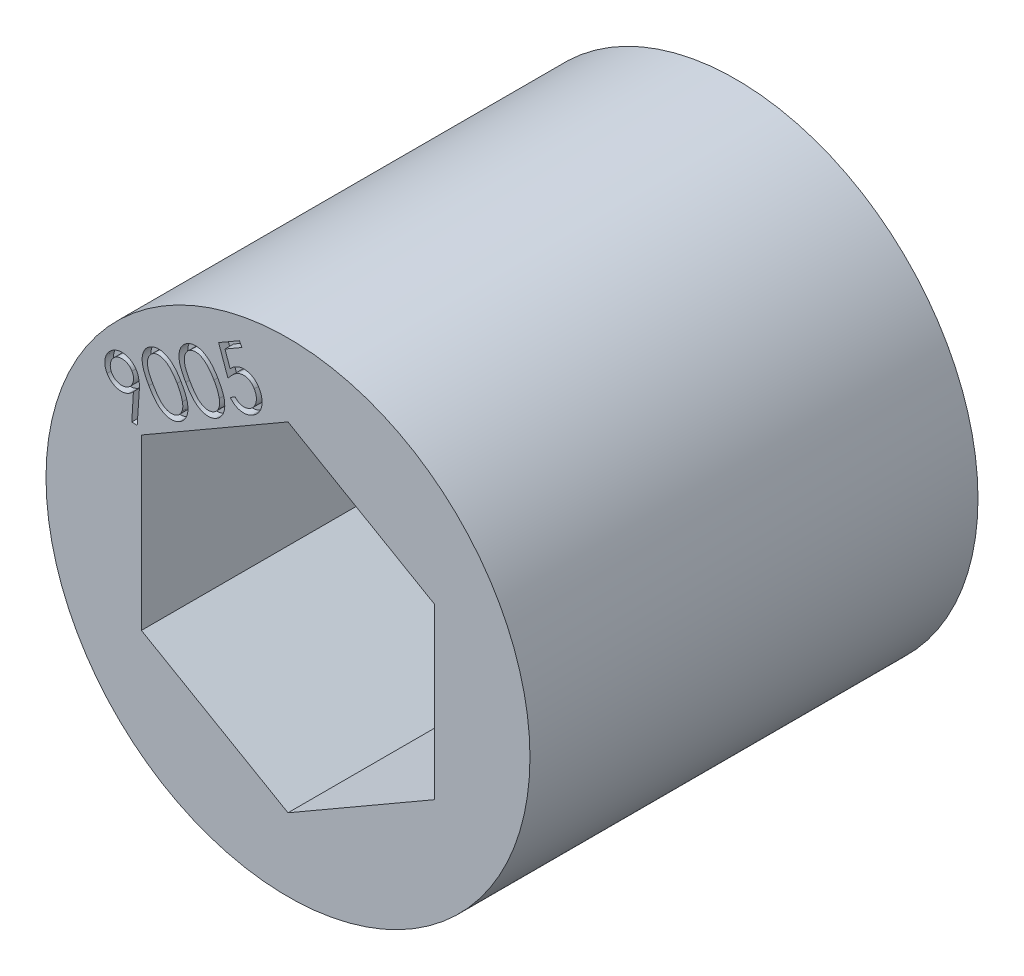
SolidWorks part; units mm, degrees
material "ABS"
ref_plane "Front Plane" through (0, 0, 0) normal (0, 0, 1) x (1, 0, 0)
ref_plane "Top Plane" through (0, 0, 0) normal (0, 1, 0) x (1, 0, 0)
ref_plane "Right Plane" through (0, 0, 0) normal (1, 0, 0) x (0, 0, -1)
sketch "Sketch1" plane through (0, 0, 0) normal (0, 0, 1) x (1, 0, 0)
  line L1 (0, 7.7723) -> (-6.731, 3.8861)
  line L2 (-6.731, 3.8861) -> (-6.731, -3.8861)
  line L3 (-6.731, -3.8861) -> (0, -7.7723)
  line L4 (0, -7.7723) -> (6.731, -3.8861)
  line L5 (6.731, -3.8861) -> (6.731, 3.8861)
  line L6 (6.731, 3.8861) -> (0, 7.7723)
  circle A0 centre (0, 0) radius 6.731 construction
  circle A1 centre (0, 0) radius 11.1125
  dimension "D1" = 13.462
  dimension "D2" = 22.225
extrude "Boss-Extrude1" add sketch "Sketch1" along normal blind 20.574 contours A1 L6 L5 L4 L3 L2 L1
sketch "Sketch2" plane through (0, 0, 20.574) normal (0, 0, 1) x (1, 0, 0)
  line L0 (-7.5438, 3.8861) -> (-0.8128, 7.7723) construction
  line L1 (0, 7.7723) -> (-6.731, 3.8861) construction
  text T0 "9005\r\n" font "Century Gothic" height 2.54
  dimension "D1" = 0.4064
extrude "Cut-Extrude1" cut sketch "Sketch2" against normal blind 0.4
